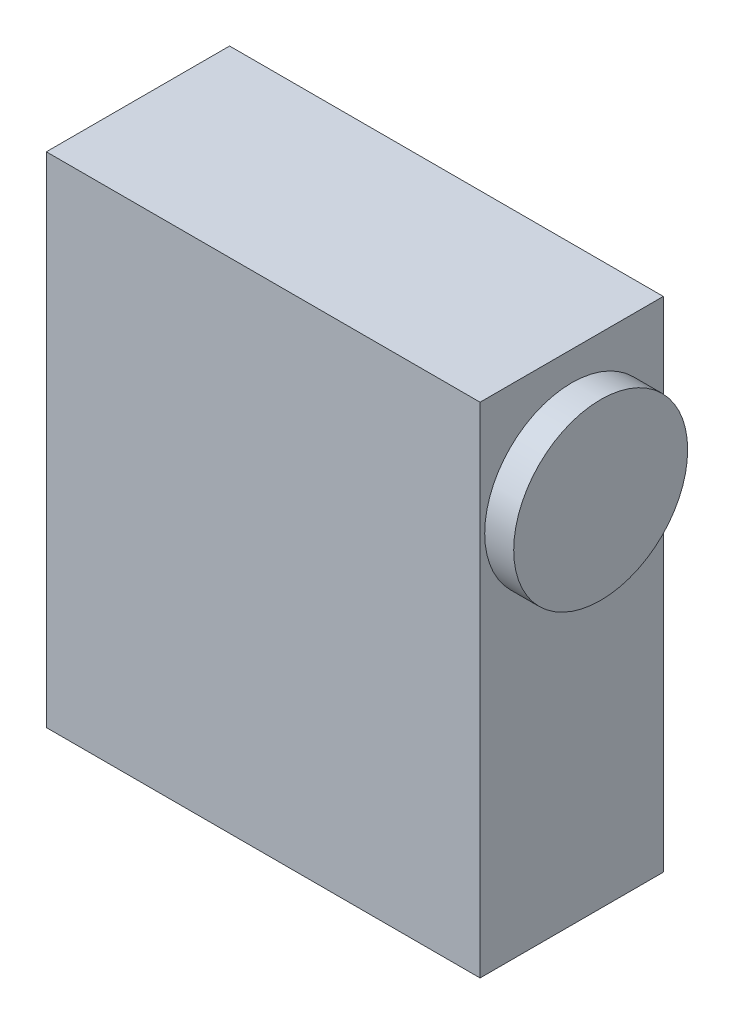
SolidWorks part; units mm, degrees
ref_plane "Front Plane" through (0, 0, 0) normal (0, 0, 1) x (1, 0, 0)
ref_plane "Top Plane" through (0, 0, 0) normal (0, 1, 0) x (1, 0, 0)
ref_plane "Right Plane" through (0, 0, 0) normal (1, 0, 0) x (0, 0, -1)
sketch "Sketch1" plane through (0, 0, 0) normal (0, 1, 0) x (1, 0, 0)
  line L1 (0, 0) -> (47.498, 0)
  line L2 (0, 0) -> (0, 20.066)
  line L3 (0, 20.066) -> (47.498, 20.066)
  line L4 (47.498, 0) -> (47.498, 20.066)
  line L5 (23.749, 20.066) -> (23.749, 0) construction
  line L6 (0, 10.033) -> (47.498, 10.033) construction
  point P100 (23.749, 10.033)
  dimension "D1" = 47.498
  dimension "D2" = 20.066
extrude "Boss-Extrude1" add sketch "Sketch1" along normal blind 54.61 contours L3 L4 L1 L2
sketch "Sketch2" plane through (47.498, 0, 0) normal (1, 0, 0) x (0, 0, -1)
  line L0 (0, 54.61) -> (20.066, 54.61) construction
  circle A0 centre (10.033, 41.91) radius 9.525
  point P6 (10.033, 54.61)
  dimension "D1" = 19.05
  dimension "D2" = 12.7
extrude "Boss-Extrude2" add sketch "Sketch2" along normal blind 3.175 contours A0
